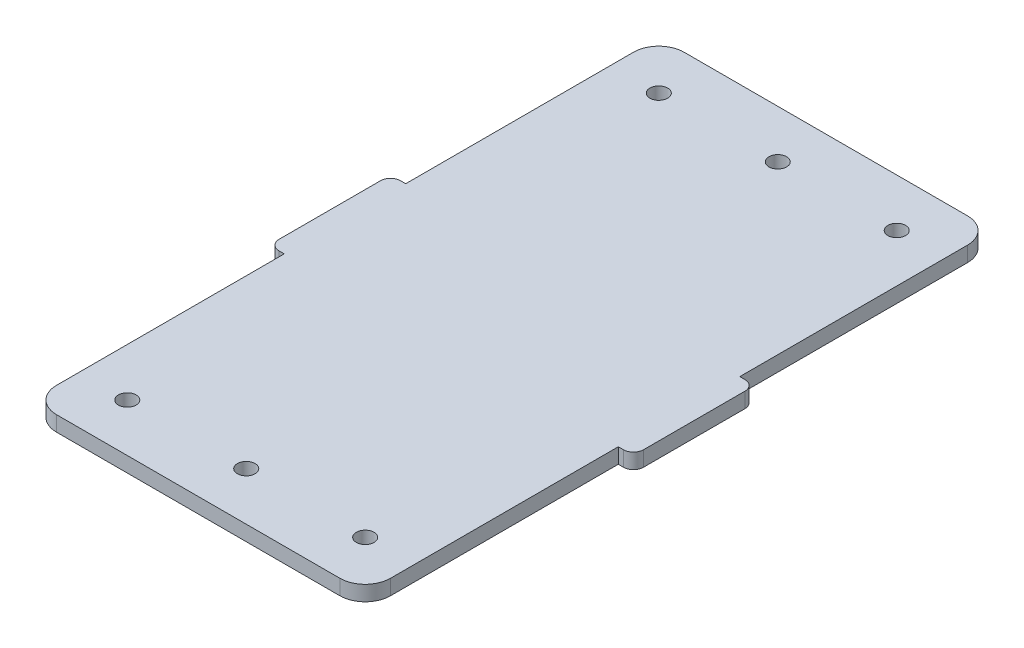
SolidWorks part; units mm, degrees
ref_plane "前视基准面" through (0, 0, 0) normal (0, 0, 1) x (1, 0, 0)
ref_plane "上视基准面" through (0, 0, 0) normal (0, 1, 0) x (1, 0, 0)
ref_plane "右视基准面" through (0, 0, 0) normal (1, 0, 0) x (0, 0, -1)
sketch "草图1" plane through (0, 0, 0) normal (0, 1, 0) x (1, 0, 0)
  line L1 (-36, 50) -> (36, 50)
  line L2 (-36, 50) -> (-36, -50)
  line L3 (-36, -50) -> (36, -50)
  line L4 (36, 50) -> (36, -50)
  line L5 (-36, 50) -> (36, -50) construction
  line L6 (-36, -50) -> (36, 50) construction
  point P0 (0, 0)
  dimension "D1" = 100
  dimension "D2" = 72
extrude "凸台-拉伸1" add sketch "草图1" along normal blind 3
sketch "草图2" plane through (0, 0, 50) normal (0, 0, 1) x (1, 0, 0)
  line L4 (-36, 0) -> (36, 0)
  line L5 (36, 0) -> (36, 3)
  line L6 (36, 3) -> (-36, 3)
  line L7 (-36, 3) -> (-36, 0)
  line L8 (-36, 0) -> (36, 0)
  line L9 (36, 0) -> (36, 3)
  line L10 (36, 3) -> (-36, 3)
  line L11 (-36, 3) -> (-36, 0)
  dimension "D1" = 0
extrude "凸台-拉伸2" add sketch "草图2" along normal blind 24
sketch "草图3" plane through (0, 3, 0) normal (0, 1, 0) x (1, 0, 0)
  line L1 (-36, 50) -> (-33, 50)
  line L2 (-36, 50) -> (-36, 0)
  line L3 (-36, 0) -> (-33, 0)
  line L4 (-33, 50) -> (-33, 0)
  line L5 (36, 50) -> (33, 50)
  line L6 (36, 50) -> (36, 0)
  line L7 (36, 0) -> (33, 0)
  line L8 (33, 50) -> (33, 0)
  line L9 (-36, -74) -> (-33, -74)
  line L10 (-36, -74) -> (-36, -24)
  line L11 (-36, -24) -> (-33, -24)
  line L12 (-33, -74) -> (-33, -24)
  line L13 (36, -74) -> (33, -74)
  line L14 (36, -74) -> (36, -24)
  line L15 (36, -24) -> (33, -24)
  line L16 (33, -74) -> (33, -24)
  dimension "D1" = 50
  dimension "D2" = 3
  dimension "D3" = 3
  dimension "D4" = 50
  dimension "D5" = 3
  dimension "D6" = 3
extrude "切除-拉伸1" cut sketch "草图3" against normal through all both and the other way through all
sketch "草图5" plane through (0, 3, 0) normal (0, 1, 0) x (1, 0, 0)
  line L0 (33, 50) -> (-33, 50) construction
  line L1 (-33, 0) -> (-33, 50) construction
  circle A0 centre (-23.5, 40.5) radius 1.75
  dimension "D1" = 3.5
  dimension "D2" = 9.5
  dimension "D3" = 9.5
extrude "切除-拉伸2" cut sketch "草图5" against normal through all both and the other way through all
sketch "草图6" plane through (0, 3, 0) normal (0, 1, 0) x (1, 0, 0)
  line L0 (33, 50) -> (-33, 50) construction
  line L1 (33, 50) -> (33, 0) construction
  line L2 (-33, -74) -> (-33, -24) construction
  line L3 (33, -74) -> (-33, -74) construction
  line L4 (33, -24) -> (33, -74) construction
  circle A0 centre (23.5, 40.5) radius 1.75
  circle A1 centre (-23.5, -64.5) radius 1.75
  circle A2 centre (23.5, -64.5) radius 1.75
  dimension "D1" = 3.5
  dimension "D4" = 9.5
  dimension "D5" = 9.5
  dimension "D6" = 9.5
  dimension "D7" = 3.5
  dimension "D8" = 3.5
  dimension "D9" = 9.5
  dimension "D2" = 9.5
  dimension "D3" = 9.5
extrude "切除-拉伸3" cut sketch "草图6" against normal through all both and the other way through all
fillet "圆角1" radius 5 4 edges at (-33, 1.5, 74) (33, 1.5, 74) (33, 1.5, -50) (-33, 1.5, -50)
fillet "圆角2" radius 2 4 edges at (36, 1.5, 24) (36, 1.5, 0) (-36, 1.5, 24) (-36, 1.5, 0)
sketch "草图8" plane through (0, 3, 0) normal (0, 1, 0) x (1, 0, 0)
  line L0 (0, 50) -> (0, -74) construction
  line L1 (28, 50) -> (-28, 50) construction
  line L2 (28, -74) -> (-28, -74) construction
  circle A0 centre (0, 40.5) radius 1.75
  circle A1 centre (0, -64.5) radius 1.75
  dimension "D1" = 3.5
  dimension "D3" = 3.5
  dimension "D4" = 9.5
  dimension "D2" = 9.5
extrude "切除-拉伸5" cut sketch "草图8" against normal through all both and the other way through all
